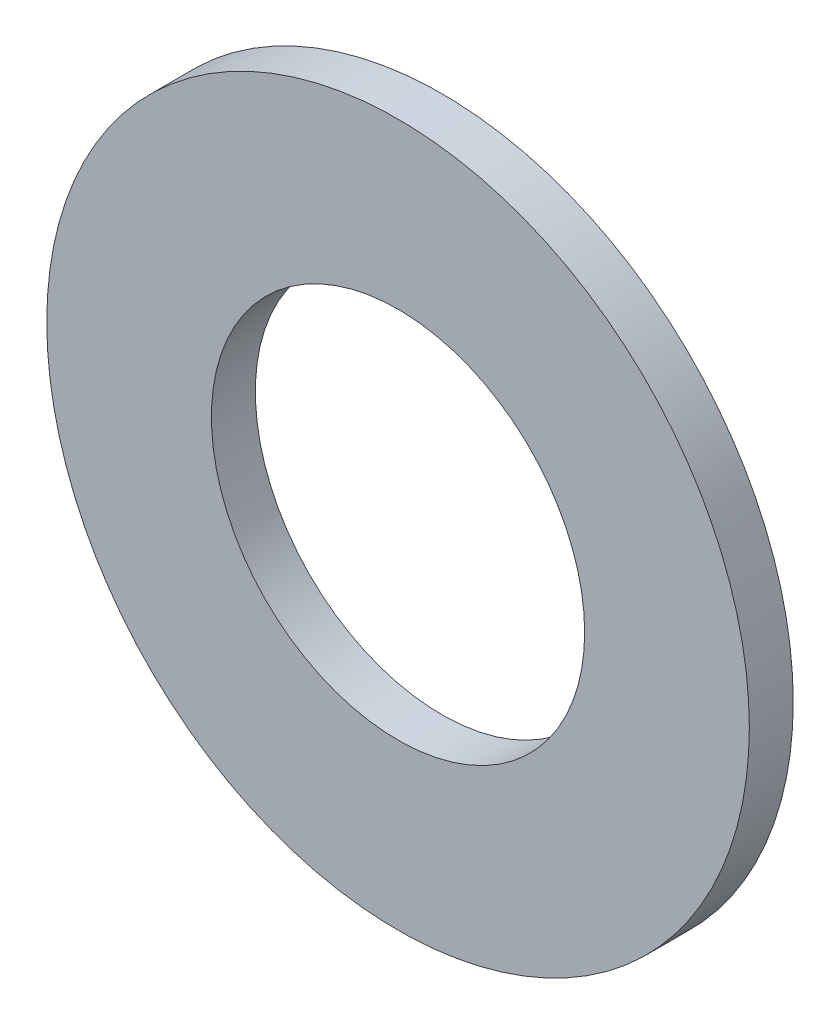
SolidWorks part; units mm, degrees
ref_plane "Plan de face" through (0, 0, 0) normal (0, 0, 1) x (1, 0, 0)
ref_plane "Plan de dessus" through (0, 0, 0) normal (0, 1, 0) x (1, 0, 0)
ref_plane "Plan de droite" through (0, 0, 0) normal (1, 0, 0) x (0, 0, -1)
sketch "Esquisse1" plane through (0, 0, 0) normal (0, 0, 1) x (1, 0, 0)
  circle A0 centre (0, 0) radius 8
  circle A1 centre (0, 0) radius 4.25
  dimension "D1" = 8.5
  dimension "D2" = 16
extrude "Boss.-Extru.1" add sketch "Esquisse1" along normal blind 1
